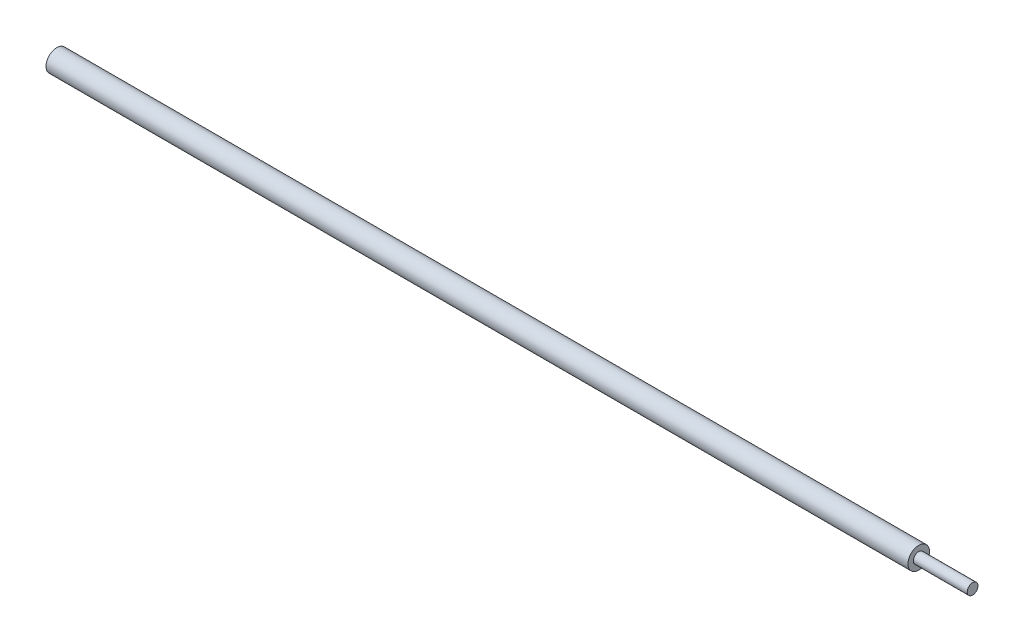
SolidWorks part; units mm, degrees
material "Natural Rubber"
ref_plane "Front Plane" through (0, 0, 0) normal (0, 0, 1) x (1, 0, 0)
ref_plane "Top Plane" through (0, 0, 0) normal (0, 1, 0) x (1, 0, 0)
ref_plane "Right Plane" through (0, 0, 0) normal (1, 0, 0) x (0, 0, -1)
sketch "Sketch1" plane through (0, 0, 0) normal (0, 0, 1) x (1, 0, 0)
  line L0 (-36.7146, 0) -> (43.2854, 0)
  dimension "D1" = 80
revolve "Revolve-Thin1" add sketch "Sketch1" angle 360 about L0 wall 1
sketch "Sketch2" plane through (43.2854, 0, 0) normal (1, 0, 0) x (0, 0, -1)
  circle A0 centre (0, 0) radius 0.5
  dimension "D1" = 1
extrude "Boss-Extrude1" add sketch "Sketch2" along normal blind 5
